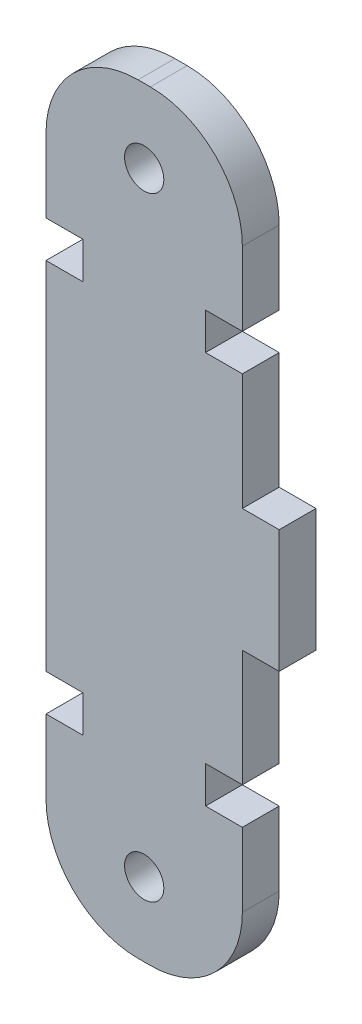
SolidWorks part; units mm, degrees
material "MDF"
ref_plane "Plano frontal" through (0, 0, 0) normal (0, 0, 1) x (1, 0, 0)
ref_plane "Plano superior" through (0, 0, 0) normal (0, 1, 0) x (1, 0, 0)
ref_plane "Plano direito" through (0, 0, 0) normal (1, 0, 0) x (0, 0, -1)
sketch "Esboço1" plane through (0, 0, 0) normal (0, 0, 1) x (1, 0, 0)
  line L0 (0, 0) -> (8, 0) construction
  line L5 (-8, -14.5) -> (8, -14.5)
  line L6 (-8, -14.5) -> (-8, 14.5)
  line L11 (-8, 14.5) -> (8, 14.5)
  line L12 (8, -14.5) -> (8, 14.5)
  line L17 (-8, -14.5) -> (8, 14.5) construction
  line L18 (-8, 14.5) -> (8, -14.5) construction
  line L23 (0, 25) -> (0, -25) construction
  line L24 (5, 17.5) -> (-5, 17.5)
  line L29 (5, 17.5) -> (5, 14.5)
  line L30 (5, 14.5) -> (-5, 14.5)
  line L31 (-5, 17.5) -> (-5, 14.5)
  line L32 (5, 17.5) -> (-5, 14.5) construction
  line L33 (5, 14.5) -> (-5, 17.5) construction
  line L34 (11, -5) -> (8, -5)
  line L35 (11, -5) -> (11, 5)
  line L36 (11, 5) -> (8, 5)
  line L37 (8, -5) -> (8, 5)
  line L38 (11, -5) -> (8, 5) construction
  line L39 (11, 5) -> (8, -5) construction
  line L44 (8, 31) -> (-8, 31)
  line L45 (8, 31) -> (8, 17.5)
  line L46 (8, 17.5) -> (-8, 17.5)
  line L47 (-8, 31) -> (-8, 17.5)
  line L48 (8, 31) -> (-8, 17.5) construction
  line L49 (8, 17.5) -> (-8, 31) construction
  line L50 (5, -14.5) -> (-5, -14.5)
  line L51 (-5, -17.5) -> (-5, -14.5)
  line L52 (5, -17.5) -> (-5, -17.5)
  line L53 (5, -17.5) -> (5, -14.5)
  line L54 (8, -17.5) -> (-8, -17.5)
  line L55 (-8, -31) -> (-8, -17.5)
  line L56 (8, -31) -> (-8, -31)
  line L57 (8, -31) -> (8, -17.5)
  circle A0 centre (0, -25) radius 1.6
  circle A1 centre (0, 25) radius 1.6
  point P0 (0, 0)
  point P6 (0, 16)
  point P7 (0, 24.25)
  point P14 (9.5, 0)
  dimension "D5" = 3.2
  dimension "D1" = 8
  dimension "D2" = 3
  dimension "D3" = 10
  dimension "D4" = 29
  dimension "D6" = 50
  dimension "D7" = 8
  dimension "D10" = 6
extrude "Ressalto-extrusão1" add sketch "Esboço1" along normal blind 3
fillet "Filete1" radius 7.5 4 edges at (-8, -31, 1.5) (8, -31, 1.5) (-8, 31, 1.5) (8, 31, 1.5)
